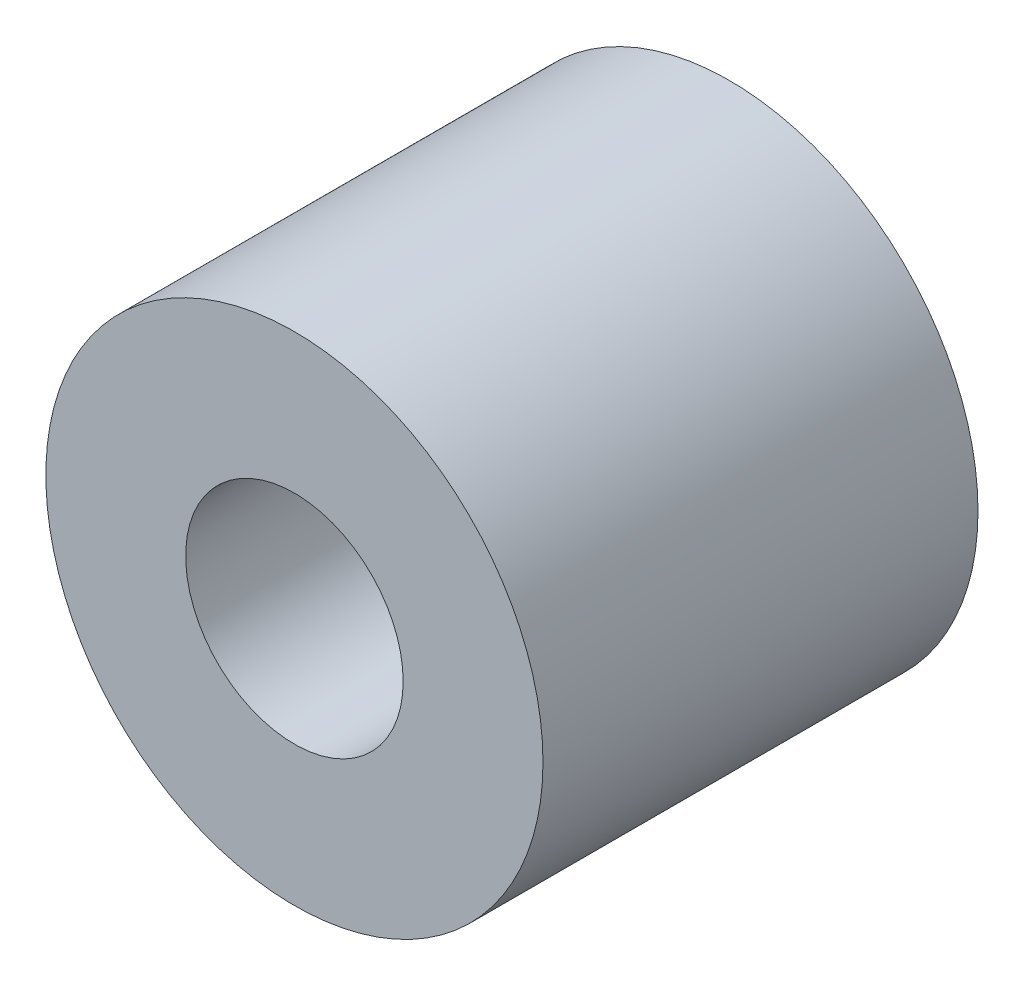
SolidWorks part; units mm, degrees
ref_plane "Front Plane" through (0, 0, 0) normal (0, 0, 1) x (1, 0, 0)
ref_plane "Top Plane" through (0, 0, 0) normal (0, 1, 0) x (1, 0, 0)
ref_plane "Right Plane" through (0, 0, 0) normal (1, 0, 0) x (0, 0, -1)
sketch "Sketch1" plane through (0, 0, 0) normal (0, 0, 1) x (1, 0, 0)
  circle A0 centre (0, 0) radius 1.75
  circle A1 centre (0, 0) radius 4
  dimension "D1" = 8
  dimension "D2" = 3.5
extrude "Boss-Extrude1" add sketch "Sketch1" along normal mid plane 7
